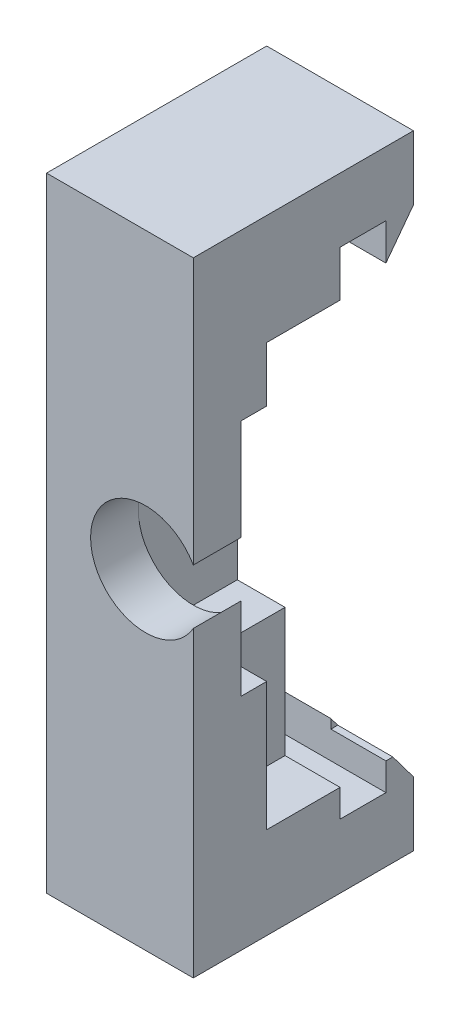
SolidWorks part; units mm, degrees
ref_plane "Front Plane" through (0, 0, 0) normal (0, 0, 1) x (1, 0, 0)
ref_plane "Top Plane" through (0, 0, 0) normal (0, 1, 0) x (1, 0, 0)
ref_plane "Right Plane" through (0, 0, 0) normal (1, 0, 0) x (0, 0, -1)
sketch "Sketch1" plane through (0, 0, 0) normal (0, 0, 1) x (1, 0, 0)
  line L1 (0, 0) -> (4, 0)
  line L2 (0, 0) -> (0, 17)
  line L3 (0, 17) -> (4, 17)
  line L4 (4, 0) -> (4, 17)
  dimension "D1" = 17
  dimension "D2" = 4
extrude "Boss-Extrude1" add sketch "Sketch1" along normal blind 6
sketch "Sketch2" plane through (0, 0, 6) normal (0, 0, 1) x (1, 0, 0)
  line L0 (4, 0) -> (4, 17) construction
  line L1 (4, 12.5) -> (1.2, 12.5)
  line L2 (4, 12.5) -> (4, 6)
  line L3 (4, 6) -> (1.2, 6)
  line L4 (1.2, 12.5) -> (1.2, 6)
  line L5 (4, 17) -> (0, 17) construction
  line L6 (0, 0) -> (4, 0) construction
  line L7 (0, 17) -> (0, 0) construction
  line L9 (4, 5.25) -> (2.5, 5.25)
  line L10 (4, 5.25) -> (4, 2.5)
  line L11 (4, 2.5) -> (2.5, 2.5)
  line L12 (2.5, 5.25) -> (2.5, 2.5)
  point P6 (2.6, 12.5)
  dimension "D1" = 4.5
  dimension "D2" = 6
  dimension "D3" = 1.2
  dimension "D4" = 1.5
  dimension "D5" = 2.5
  dimension "D6" = 0.75
extrude "Cut-Extrude1" cut sketch "Sketch2" against normal through all
sketch "Sketch3" plane through (0, 0, 0) normal (-1, 0, 0) x (0, 0, 1)
  line L0 (0, 15.25) -> (0.75, 14.25)
  line L1 (0, 17) -> (0, 0) construction
  line L2 (0.75, 14.25) -> (0.75, 15.25)
  line L3 (0.75, 15.25) -> (2, 15.25)
  line L4 (2, 15.25) -> (2, 1.75)
  line L5 (0, 15.25) -> (0, 1.75)
  line L6 (-999.8573, 8.5) -> (49000.1427, 8.5) construction
  line L7 (6, 17) -> (0, 17) construction
  line L8 (6, 17) -> (6, 0) construction
  line L9 (0.75, 1.75) -> (2, 1.75)
  line L10 (0.75, 2.75) -> (0.75, 1.75)
  line L11 (0, 1.75) -> (0.75, 2.75)
  point P17 (0, 8.5)
  point P18 (2, 8.5)
  dimension "D1" = 1.75
  dimension "D2" = 4
  dimension "D3" = 1.25
  dimension "D4" = 1.75
  dimension "D5" = 1
extrude "Cut-Extrude2" cut sketch "Sketch3" against normal through all
sketch "Sketch4" plane through (4, 0, 0) normal (1, 0, 0) x (0, 0, -1)
  line L0 (-2, 2.5) -> (-6, 2.5) construction
  line L1 (-6, 5.25) -> (-4, 5.25)
  line L2 (-6, 5.25) -> (-6, 2.5)
  line L3 (-6, 2.5) -> (-4, 2.5)
  line L4 (-4, 5.25) -> (-4, 2.5)
  dimension "D1" = 2
extrude "Boss-Extrude2" add sketch "Sketch4" against normal blind 2
sketch "Sketch6" plane through (0, 0, 2) normal (0, 0, -1) x (-1, 0, 0)
  line L1 (-4, 12.5) -> (-2.5, 12.5)
  line L2 (-4, 12.5) -> (-4, 14)
  line L3 (-4, 14) -> (-2.5, 14)
  line L4 (-2.5, 12.5) -> (-2.5, 14)
  line L5 (-2.5, 5.25) -> (-4, 5.25)
  line L6 (-2.5, 5.25) -> (-2.5, 6)
  line L7 (-2.5, 6) -> (-4, 6)
  line L8 (-4, 5.25) -> (-4, 6)
  dimension "D1" = 1.5
  dimension "D2" = 1.5
extrude "Cut-Extrude3" cut sketch "Sketch6" against normal blind 2
sketch "Sketch7" plane through (1.2, 0, 0) normal (1, 0, 0) x (0, 0, -1)
  line L0 (-2, 6) -> (-6, 6) construction
  line L1 (-6, 12.5) -> (-4.7, 12.5)
  line L2 (-6, 12.5) -> (-6, 6)
  line L3 (-6, 6) -> (-4.7, 6)
  line L4 (-4.7, 12.5) -> (-4.7, 6)
  line L5 (-2, 6) -> (-2, 12.5) construction
  dimension "D1" = 2.7
extrude "Boss-Extrude3" add sketch "Sketch7" along normal up to surface (2.8 mm away) up to face at (4, 14.7, 2.55)
sketch "Sketch8" plane through (0, 0, 4.7) normal (0, 0, -1) x (-1, 0, 0)
  line L0 (-4, 17) -> (0, 17) construction
  line L1 (-1.2, 6) -> (-1.2, 12.5) construction
  circle A0 centre (-2.7, 9) radius 1.5
  dimension "D2" = 3
  dimension "D1" = 8
  dimension "D3" = 1.5
extrude "Cut-Extrude4" cut sketch "Sketch8" against normal blind 10
